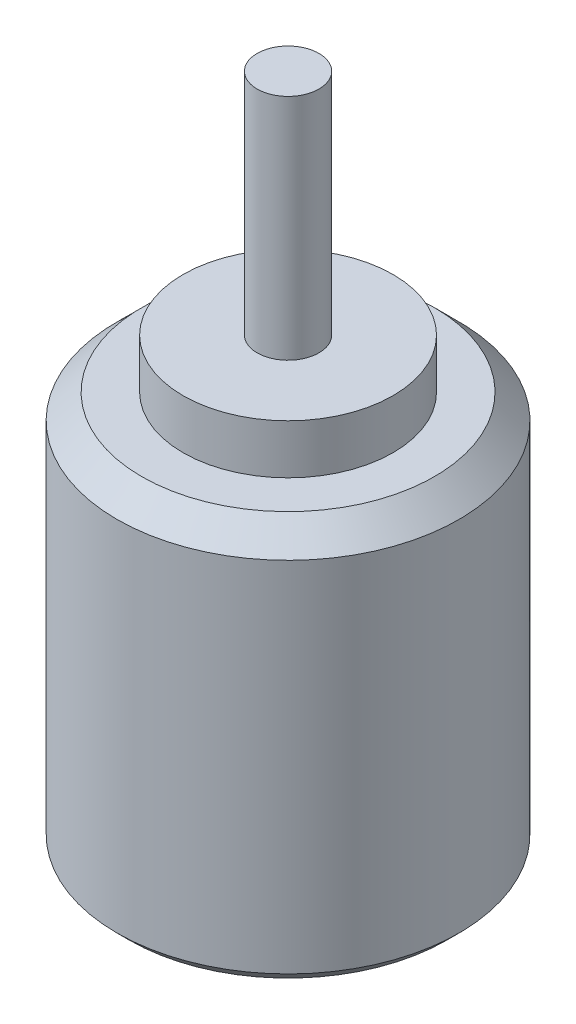
SolidWorks part; units mm, degrees
ref_plane "前视基准面" through (0, 0, 0) normal (0, 0, 1) x (1, 0, 0)
ref_plane "上视基准面" through (0, 0, 0) normal (0, 1, 0) x (1, 0, 0)
ref_plane "右视基准面" through (0, 0, 0) normal (1, 0, 0) x (0, 0, -1)
sketch "草图1" plane through (0, 0, 0) normal (0, 1, 0) x (1, 0, 0)
  circle A0 centre (0, 0) radius 13.85
  dimension "D1" = 27.7
extrude "凸台-拉伸1" add sketch "草图1" along normal blind 32
sketch "草图2" plane through (0, 0, 0) normal (0, -1, 0) x (1, 0, 0)
  circle A0 centre (0, 0) radius 2.5
  dimension "D1" = 5
extrude "凸台-拉伸2" add sketch "草图2" along normal blind 2.5
sketch "草图3" plane through (0, 32, 0) normal (0, 1, 0) x (1, 0, 0)
  circle A0 centre (0, 0) radius 8.5
  dimension "D1" = 17
extrude "凸台-拉伸3" add sketch "草图3" along normal blind 4
sketch "草图4" plane through (0, 36, 0) normal (0, 1, 0) x (1, 0, 0)
  circle A0 centre (0, 0) radius 2.5
  dimension "D1" = 5
extrude "凸台-拉伸4" add sketch "草图4" along normal blind 18.5
chamfer "倒角1" distance 2 angle 45 1 edges at (0, 32, 13.85)
chamfer "倒角2" distance 1 angle 45 1 edges at (0, 0, 13.85)
sketch "草图5" plane through (0, 0, 0) normal (0, -1, 0) x (1, 0, 0)
  line L0 (-9.5, 0) -> (9.5, 0) construction
  line L1 (0, 8) -> (0, -8) construction
  circle A0 centre (0, 8) radius 1.35
  circle A1 centre (-9.5, 0) radius 1.35
  circle A2 centre (0, -8) radius 1.35
  circle A3 centre (9.5, 0) radius 1.35
  point P5 (0, 0)
  point P9 (0, 0)
  dimension "D3" = 2.7
  dimension "D1" = 16
  dimension "D2" = 19
extrude "切除-拉伸1" cut sketch "草图5" against normal blind 3
